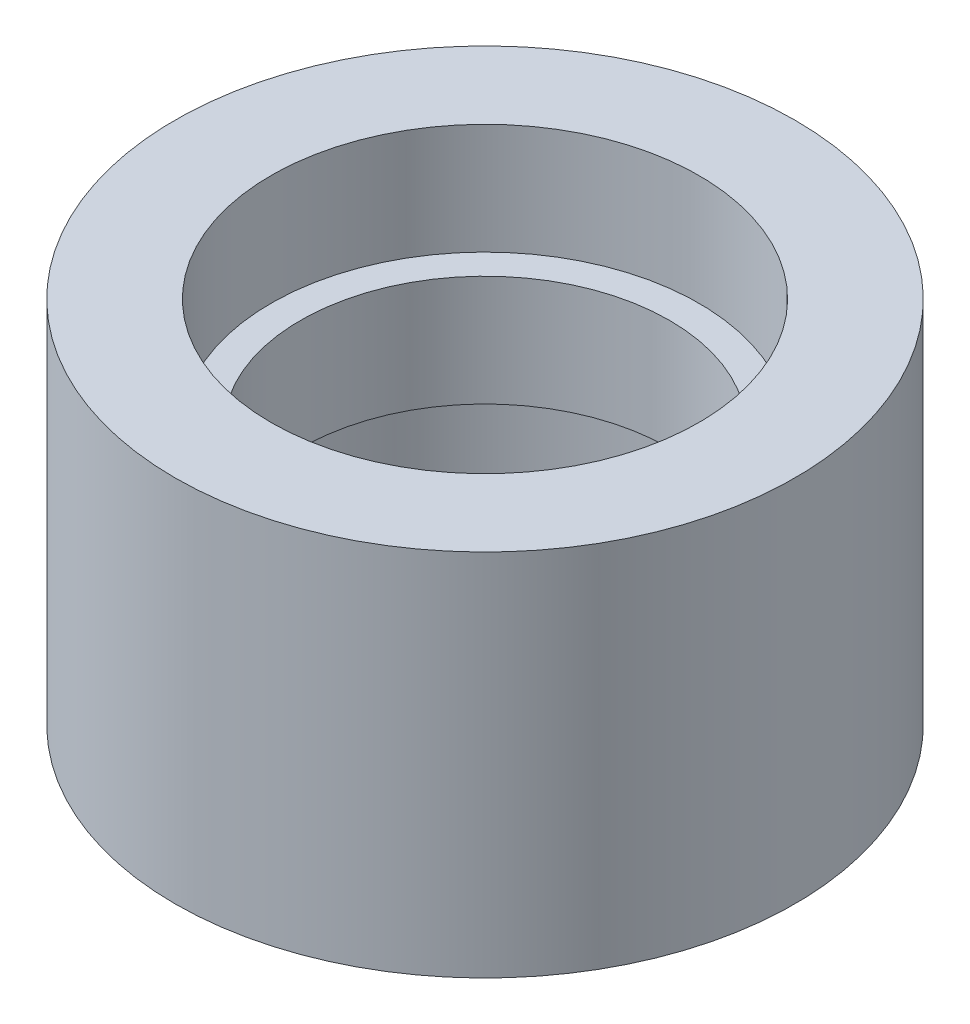
SolidWorks part; units mm, degrees
material "AISI 304"
ref_plane "前视基准面" through (0, 0, 0) normal (0, 0, 1) x (1, 0, 0)
ref_plane "上视基准面" through (0, 0, 0) normal (0, 1, 0) x (1, 0, 0)
ref_plane "右视基准面" through (0, 0, 0) normal (1, 0, 0) x (0, 0, -1)
sketch "Sketch1" plane through (0, 0, 0) normal (0, 1, 0) x (1, 0, 0)
  circle A0 centre (0, 0) radius 25
  circle A1 centre (0, 0) radius 42
  dimension "D1" = 84
  dimension "D2" = 50
extrude "Extrude1" add sketch "Sketch1" along normal blind 50
sketch "Sketch2" plane through (0, 50, 0) normal (0, 1, 0) x (1, 0, 0)
  circle A0 centre (0, 0) radius 47.5
  dimension "D1" = 95
sketch "Sketch3" plane through (0, 50, 0) normal (0, 1, 0) x (1, 0, 0)
  circle A0 centre (0, 0) radius 29
  dimension "D1" = 58
extrude "Extrude3" cut sketch "Sketch3" against normal blind 15
sketch "Sketch4" plane through (0, 0, 0) normal (0, -1, 0) x (1, 0, 0)
  circle A0 centre (0, 0) radius 29
  dimension "D1" = 58
extrude "Extrude4" cut sketch "Sketch4" against normal blind 20
sketch "Sketch5" plane through (0, 0, 0) normal (0, -1, 0) x (1, 0, 0)
  circle A0 centre (0, 0) radius 31
  dimension "D1" = 62
extrude "Extrude5" cut sketch "Sketch5" against normal blind 9
sketch "Sketch6" plane through (0, 0, 0) normal (0, -1, 0) x (1, 0, 0)
  line L1 (24, -24) -> (-24, -24) construction
  line L2 (24, -24) -> (24, 24) construction
  line L3 (24, 24) -> (-24, 24) construction
  line L4 (-24, -24) -> (-24, 24) construction
  line L5 (24, -24) -> (-24, 24) construction
  line L6 (24, 24) -> (-24, -24) construction
  point P0 (0, 0)
  dimension "D1" = 48
hole_wizard "M4 Tapped Hole1" positions "3DSketch1" profile "Sketch7" tap size "M4" standard "GB"
sketch3d "3DSketch1"
  point P0 (-24, 0, 24)
  point P3 (24, 0, 24)
  point P6 (-24, 0, -24)
  point P9 (24, 0, -24)
sketch "Sketch7" plane through (-24, 0, 24) normal (1, 0, 0) x (0, 0, -1)
  line L0 (0, 0) -> (0, 11.0914)
  line L1 (0, 11.0914) -> (1.65, 10.1)
  line L2 (1.65, 10.1) -> (1.65, 0)
  line L5 (1.65, 0) -> (0, 0)
  line L10 (0, 11.0914) -> (-1.65, 10.1) construction
  line L11 (0, -6.35) -> (0, 107.95) construction
  dimension "螺纹孔钻头直径" = 3.3
  dimension "螺纹孔钻头深度" = 10.1
  dimension "导头角度" = 118
cosmetic thread "Cosmetic Thread5" parameters "D1"=8, "D2"=4
cosmetic thread "Cosmetic Thread6" parameters "D1"=8, "D2"=4
cosmetic thread "Cosmetic Thread7" parameters "D1"=8, "D2"=4
cosmetic thread "Cosmetic Thread8" parameters "D1"=8, "D2"=4
